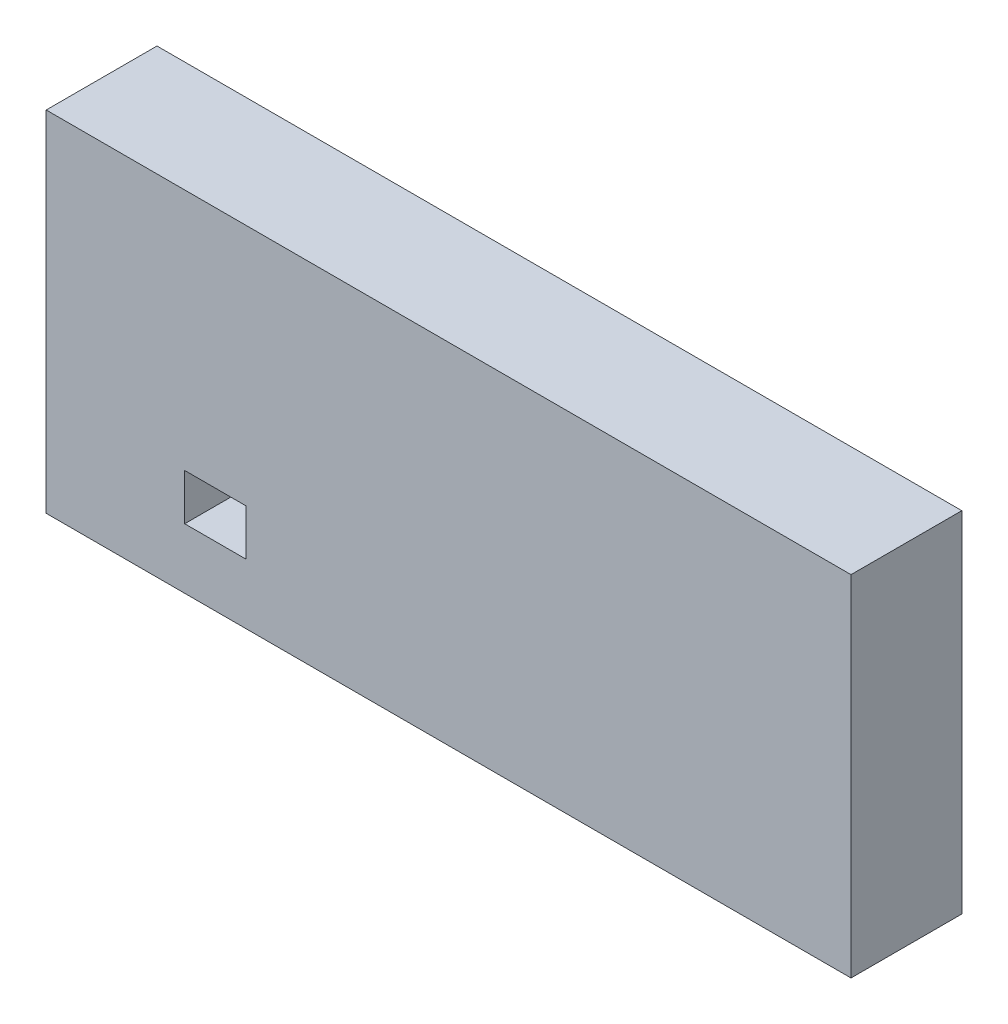
SolidWorks part; units mm, degrees
ref_plane "前视基准面" through (0, 0, 0) normal (0, 0, 1) x (1, 0, 0)
ref_plane "上视基准面" through (0, 0, 0) normal (0, 1, 0) x (1, 0, 0)
ref_plane "右视基准面" through (0, 0, 0) normal (1, 0, 0) x (0, 0, -1)
other "Configuration Table"
sketch "草图1" plane through (0, 0, 0) normal (0, 0, 1) x (1, 0, 0)
  line L1 (-36.4749, 15.89) -> (15.8251, 15.89)
  line L2 (-36.4749, 15.89) -> (-36.4749, -6.81)
  line L3 (-36.4749, -6.81) -> (15.8251, -6.81)
  line L4 (15.8251, 15.89) -> (15.8251, -6.81)
  dimension "D1" = 22.7
  dimension "D2" = 52.3
extrude "凸台-拉伸1" add sketch "草图1" along normal blind 7.2
sketch "草图2" plane through (0, 0, 0) normal (0, 0, -1) x (-1, 0, 0)
  line L0 (36.4749, -6.81) -> (-15.8251, -6.81) construction
  line L1 (-9.6251, -4.31) -> (30.9749, -4.31)
  line L2 (-9.6251, -4.31) -> (-9.6251, -6.81)
  line L3 (-9.6251, -6.81) -> (30.9749, -6.81)
  line L4 (30.9749, -4.31) -> (30.9749, -6.81)
  line L5 (36.4749, 15.89) -> (36.4749, -6.81) construction
  line L6 (-15.8251, 15.89) -> (36.4749, 15.89) construction
  dimension "D1" = 2.5
  dimension "D2" = 40.6
  dimension "D3" = 5.5
  dimension "D4" = 52.3
extrude "凸台-拉伸2" add sketch "草图2" along normal blind 2
sketch "草图3" plane through (-36.4749, 0, 0) normal (-1, 0, 0) x (0, 0, 1)
  line L3 (1, 15.89) -> (1, -5.6268) construction
  line L5 (0, 15.89) -> (0, -6.81) construction
  line L6 (2.5, 8.54) -> (2.5, 0.54) construction
  line L7 (4, 8.54) -> (4, 0.54)
  line L8 (1, 8.54) -> (1, 0.54)
  line L9 (0, 4.54) -> (16.1179, 4.54) construction
  arc A0 (4, 8.54) -> (1, 8.54) centre (2.5, 8.54) ccw
  arc A1 (1, 0.54) -> (4, 0.54) centre (2.5, 0.54) ccw
  point P8 (2.5, 4.54)
  dimension "D3" = 8
  dimension "D1" = 1
  dimension "D2" = 3
  dimension "D4" = 0
  dimension "D5" = 0
sketch "草图5" plane through (-36.4749, 0, 0) normal (-1, 0, 0) x (0, 0, 1)
  line L0 (4, 8.54) -> (4, 0.54) construction
  line L1 (4, 8.54) -> (4, 0.54)
  line L2 (1, 8.54) -> (1, 0.54) construction
  line L3 (1, 8.54) -> (1, 0.54)
  arc A0 (1, 0.54) -> (4, 0.54) centre (2.5, 0.54) ccw construction
  arc A1 (4, 8.54) -> (1, 8.54) centre (2.5, 8.54) ccw construction
  arc A2 (1, 0.54) -> (4, 0.54) centre (2.5, 0.54) ccw
  arc A3 (4, 8.54) -> (1, 8.54) centre (2.5, 8.54) ccw
extrude "凸台-拉伸3" add sketch "草图5" along normal blind 1
sketch "草图9" plane through (0, 0, 7.2) normal (0, 0, 1) x (1, 0, 0)
  line L1 (-27.4749, 0.1036) -> (-23.4749, 0.1036)
  line L2 (-27.4749, 0.1036) -> (-27.4749, -2.8964)
  line L3 (-27.4749, -2.8964) -> (-23.4749, -2.8964)
  line L4 (-23.4749, 0.1036) -> (-23.4749, -2.8964)
  line L5 (-36.4749, 200015.89) -> (-36.4749, -200005.6268) construction
  dimension "D1" = 13
  dimension "D2" = 4
  dimension "D3" = 3
extrude "切除-拉伸1" cut sketch "草图9" against normal blind 3.6
